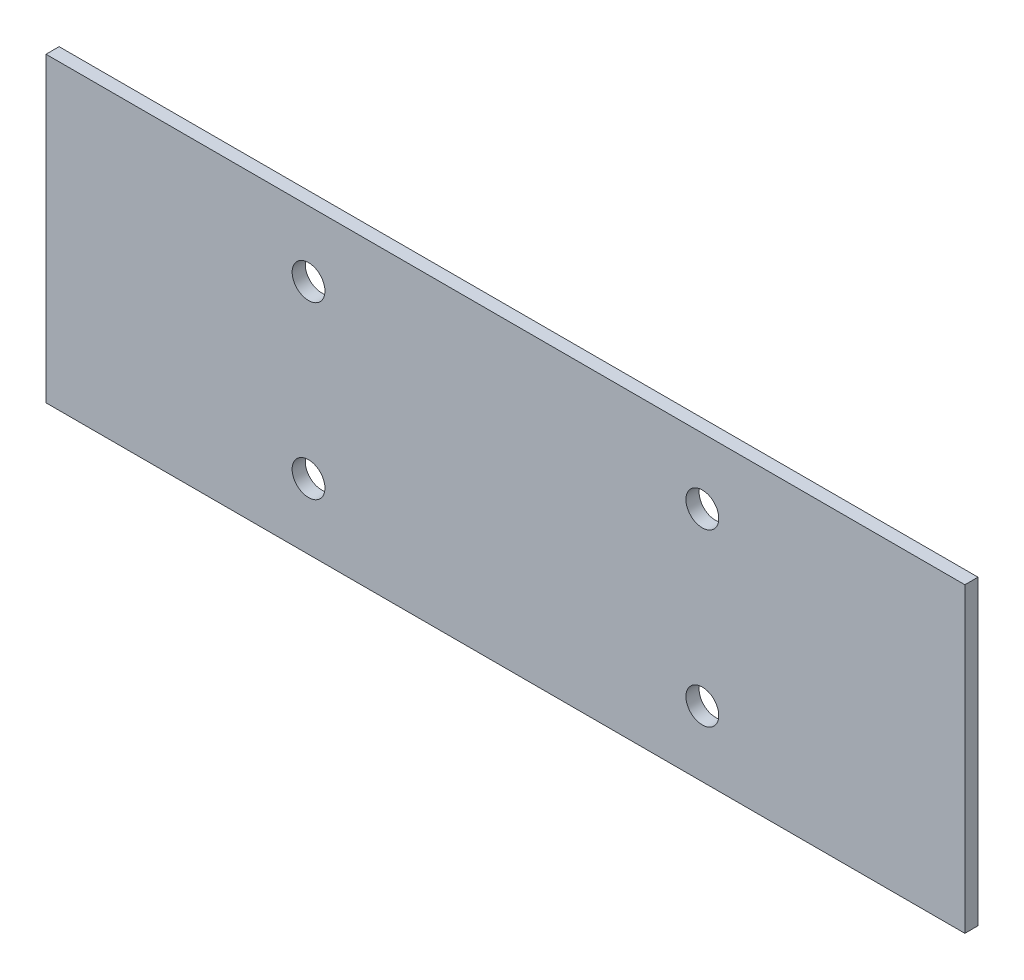
SolidWorks part; units mm, degrees
ref_plane "Ön Düzlem" through (0, 0, 0) normal (0, 0, 1) x (1, 0, 0)
ref_plane "Üst Düzlem" through (0, 0, 0) normal (0, 1, 0) x (1, 0, 0)
ref_plane "Sağ Düzlem" through (0, 0, 0) normal (1, 0, 0) x (0, 0, -1)
sketch "Çizim1" plane through (0, 0, 0) normal (0, 0, 1) x (1, 0, 0)
  line L1 (0, 0) -> (140, 0)
  line L2 (0, 0) -> (0, 46)
  line L3 (0, 46) -> (140, 46)
  line L4 (140, 0) -> (140, 46)
  line L5 (40, 36) -> (100, 36) construction
  line L6 (40, 36) -> (40, 10) construction
  line L7 (40, 10) -> (100, 10) construction
  line L8 (100, 36) -> (100, 10) construction
  circle A0 centre (40, 36) radius 2.5
  circle A1 centre (100, 36) radius 2.5
  circle A2 centre (40, 10) radius 2.5
  circle A3 centre (100, 10) radius 2.5
  dimension "D1" = 140
  dimension "D2" = 46
  dimension "D3" = 40
  dimension "D4" = 10
  dimension "D5" = 26
  dimension "D6" = 60
extrude "Yükseklik-Ekstrüzyon1" add sketch "Çizim1" along normal blind 2
